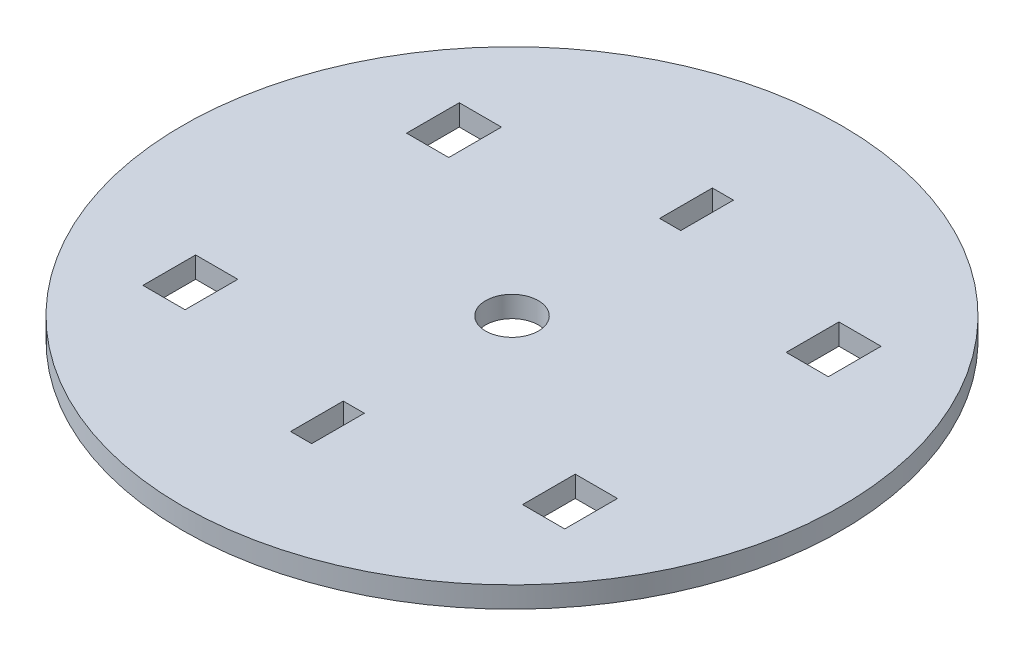
SolidWorks part; units mm, degrees
ref_plane "Front Plane" through (0, 0, 0) normal (0, 0, 1) x (1, 0, 0)
ref_plane "Top Plane" through (0, 0, 0) normal (0, 1, 0) x (1, 0, 0)
ref_plane "Right Plane" through (0, 0, 0) normal (1, 0, 0) x (0, 0, -1)
sketch "Sketch1" plane through (0, 0, 0) normal (0, 1, 0) x (1, 0, 0)
  circle A0 centre (0, 0) radius 125
  circle A1 centre (0, 0) radius 10
  dimension "D1" = 250
  dimension "D2" = 20
extrude "Boss-Extrude1" add sketch "Sketch1" along normal blind 8
sketch "Sketch2" plane through (0, 8, 0) normal (0, 1, 0) x (1, 0, 0)
  line L1 (-80, -80) -> (80, -80) construction
  line L2 (-80, -80) -> (-80, 80) construction
  line L3 (-80, 80) -> (80, 80) construction
  line L4 (80, -80) -> (80, 80) construction
  line L5 (-80, -80) -> (80, 80) construction
  line L6 (-80, 80) -> (80, -80) construction
  line L7 (-80, 60) -> (-64, 60)
  line L8 (-80, 60) -> (-80, 40)
  line L9 (-80, 40) -> (-64, 40)
  line L10 (-64, 60) -> (-64, 40)
  point P0 (0, 0)
  point P10 (-64, 50)
  dimension "D1" = 160
  dimension "D2" = 160
  dimension "D3" = 20
  dimension "D4" = 20
  dimension "D5" = 16
extrude "Cut-Extrude1" cut sketch "Sketch2" against normal blind 10
pattern_linear "LPattern1" count 2 spacing 144 along (1, 0, 0) count 2 spacing 100 along (0, 0, 1) of "Cut-Extrude1"
sketch "Sketch3" plane through (0, 8, 0) normal (0, 1, 0) x (1, 0, 0)
  line L0 (0, 0) -> (0, 125) construction
  line L2 (-4, 60) -> (4, 60)
  line L3 (-4, 60) -> (-4, 80)
  line L4 (-4, 80) -> (4, 80)
  line L5 (4, 60) -> (4, 80)
  line L6 (-4, 60) -> (4, 80) construction
  line L7 (-4, 80) -> (4, 60) construction
  circle A0 centre (0, 0) radius 125 construction
  point P6 (0, 70)
  dimension "D1" = 8
  dimension "D2" = 20
  dimension "D3" = 60
extrude "Cut-Extrude2" cut sketch "Sketch3" against normal blind 8
mirror "Mirror1" about plane through (0, 0, 0) normal (0, 0, 1) of "Cut-Extrude2"
